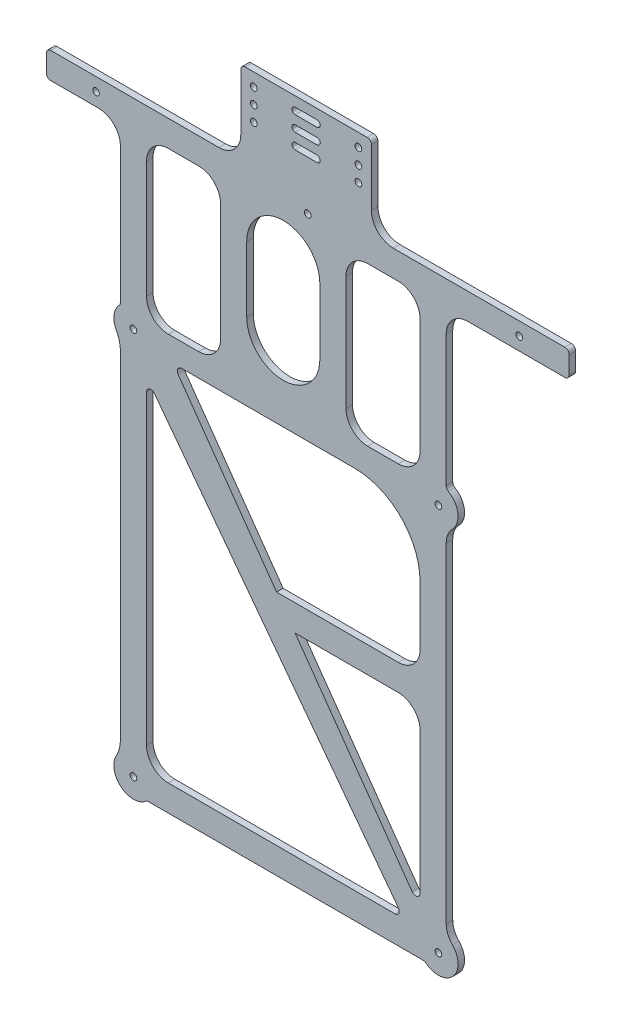
SolidWorks part; units mm, degrees
material "3.3549 (EN-AW 5182)"
ref_plane "前视基准面" through (0, 0, 0) normal (0, 0, 1) x (1, 0, 0)
ref_plane "上视基准面" through (0, 0, 0) normal (0, 1, 0) x (1, 0, 0)
ref_plane "右视基准面" through (0, 0, 0) normal (1, 0, 0) x (0, 0, -1)
other "Configuration Table"
sketch "草图1" plane through (0, 0, 0) normal (0, 0, 1) x (1, 0, 0)
  line L4 (0, 0) -> (0, 0.1191) construction
  line L5 (0, 94.7671) -> (-0.0472, 94.7671) construction
  line L9 (63.5621, 7.8739) -> (63.5621, 94.7671)
  line L10 (60, -5.4329) -> (60, 5.3453) construction
  line L12 (60, -5.4329) -> (51, -5.4329) construction
  line L17 (63.5621, 94.7671) -> (63.5621, 159.1604)
  line L18 (60, 172.4671) -> (80.26, 172.4671) construction
  line L23 (-80, 172.4671) -> (-80, 188.0766) construction
  line L24 (-86, 160.7656) -> (-86, 6.2686)
  line L28 (253.1696, 5.3453) -> (243.1696, 5.3453) construction
  line L29 (-10.7455, 186.263) -> (-10.7455, 172.4671) construction
  line L31 (304, 272.3171) -> (-304, 272.3171) construction
  line L32 (304, 272.3171) -> (304, -82.7829) construction
  line L33 (304, -82.7829) -> (-304, -82.7829) construction
  line L34 (-304, 272.3171) -> (-304, -82.7829) construction
  line L35 (304, 272.3171) -> (0, 94.7671) construction
  line L36 (304, -82.7829) -> (-304, 272.3171) construction
  line L37 (15.2545, 302.3171) -> (-28.7455, 302.3171)
  line L47 (-74, 150.5112) -> (-74, 10.0444)
  line L48 (-64, 0.0444) -> (40.001, 0.0444)
  line L49 (51.5621, 137.9092) -> (51.5621, 110.7671)
  line L50 (-57.898, 167.9092) -> (21.5621, 167.9092)
  line L51 (-70.4034, 151.7157) -> (41.5976, 3.2489)
  line L52 (47.9291, 12.7797) -> (-5.801, 88.7671)
  line L53 (118, 264.2671) -> (39.2545, 264.2671)
  line L54 (118, 252.2671) -> (73.5621, 252.2671)
  line L55 (-120, 262.2671) -> (-120, 254.2671)
  line L56 (120, 262.2671) -> (120, 254.2671)
  line L57 (17.5621, 242.2671) -> (17.5621, 189.674)
  line L58 (-40, 242.2671) -> (-40, 188.4671)
  line L59 (-50.7455, 264.2671) -> (-118, 264.2671)
  line L60 (-50, 252.2671) -> (-64, 252.2671)
  line L61 (63.5621, 242.2671) -> (63.5621, 181.9573)
  line L63 (41.5621, 252.2671) -> (27.5621, 252.2671)
  line L65 (-86, 180.0169) -> (-86, 242.2671)
  line L66 (-96, 252.2671) -> (-118, 252.2671)
  line L67 (41.5621, 100.7671) -> (-14.2861, 100.7671)
  line L68 (41.5621, 88.7671) -> (-5.801, 88.7671)
  line L69 (51.5621, 78.7671) -> (51.5621, 13.9344)
  line L70 (-14.2861, 100.7671) -> (-59.531, 164.7545)
  line L71 (-7.1081, 90.6157) -> (-304, -82.7829) construction
  line L74 (-50, 178.4671) -> (-64, 178.4671)
  line L75 (-74, 242.2671) -> (-74, 188.4671)
  line L76 (27.5621, 179.674) -> (41.5621, 179.674)
  line L78 (51.5621, 242.2671) -> (51.5621, 189.674)
  line L79 (15.2545, 302.3171) -> (19.2545, 302.3171)
  line L80 (-30.7455, 300.3171) -> (-30.7455, 274.2671)
  line L82 (-50.7455, 264.2671) -> (-40.7455, 264.2671)
  line L83 (29.2545, 274.2671) -> (29.2545, 300.3171)
  line L85 (27.2545, 302.3171) -> (19.2545, 302.3171)
  line L86 (52.9494, -11.9556) -> (-73.0456, -11.9556)
  arc A2 (66.4241, 166.1639) -> (64.5508, 180.2318) centre (60, 172.4671) ccw
  arc A4 (-86.5455, 178.6442) -> (-87.8898, 168.1369) centre (-80, 172.4671) ccw
  arc A5 (-87.8898, -1.1027) -> (-74.31, -12.406) centre (-80, -5.4329) ccw
  arc A8 (54.7482, -12.7417) -> (66.4241, 0.8703) centre (60, -5.4329) ccw
  circle A9 centre (0, 258.2671) radius 10.5322 construction
  arc A12 (27.5621, 179.674) -> (17.5621, 189.674) centre (27.5621, 189.674) cw
  arc A13 (-50, 178.4671) -> (-40, 188.4671) centre (-50, 188.4671) ccw
  arc A14 (53.9586, -12.2289) -> (54.7482, -12.7417) centre (48.9128, -20.8625) cw
  arc A15 (63.5621, 7.8739) -> (66.4241, 0.8703) centre (73.5621, 7.8739) ccw
  arc A16 (63.5621, 159.1604) -> (66.4241, 166.1639) centre (73.5621, 159.1604) cw
  arc A19 (-86, 160.7656) -> (-87.8898, 168.1369) centre (-101.3209, 160.7656) ccw
  arc A20 (-86, 6.2686) -> (-87.8898, -1.1027) centre (-101.3209, 6.2686) cw
  arc A22 (-64, 0.0444) -> (-74, 10.0444) centre (-64, 10.0444) cw
  arc A25 (21.5621, 167.9092) -> (51.5621, 137.9092) centre (21.5621, 137.9092) cw
  arc A26 (40.001, 0.0444) -> (41.5976, 3.2489) centre (40.001, 2.0444) ccw
  arc A27 (51.5621, 13.9344) -> (47.9291, 12.7797) centre (49.5621, 13.9344) cw
  arc A28 (-57.898, 167.9092) -> (-59.531, 164.7545) centre (-57.898, 165.9092) ccw
  arc A29 (-74, 150.5112) -> (-70.4034, 151.7157) centre (-72, 150.5112) cw
  arc A32 (-40, 242.2671) -> (-50, 252.2671) centre (-50, 242.2671) ccw
  arc A33 (17.5621, 242.2671) -> (27.5621, 252.2671) centre (27.5621, 242.2671) cw
  arc A34 (118, 264.2671) -> (120, 262.2671) centre (118, 262.2671) cw
  arc A35 (118, 252.2671) -> (120, 254.2671) centre (118, 254.2671) ccw
  arc A36 (-118, 264.2671) -> (-120, 262.2671) centre (-118, 262.2671) ccw
  arc A37 (-118, 252.2671) -> (-120, 254.2671) centre (-118, 254.2671) cw
  arc A38 (-64, 252.2671) -> (-74, 242.2671) centre (-64, 242.2671) ccw
  arc A39 (51.5621, 242.2671) -> (41.5621, 252.2671) centre (41.5621, 242.2671) ccw
  arc A40 (63.5621, 242.2671) -> (73.5621, 252.2671) centre (73.5621, 242.2671) cw
  arc A41 (-86, 242.2671) -> (-96, 252.2671) centre (-96, 242.2671) ccw
  arc A42 (41.5621, 88.7671) -> (51.5621, 78.7671) centre (41.5621, 78.7671) cw
  arc A43 (41.5621, 100.7671) -> (51.5621, 110.7671) centre (41.5621, 110.7671) ccw
  arc A44 (41.5621, 179.674) -> (51.5621, 189.674) centre (41.5621, 189.674) ccw
  arc A45 (-64, 178.4671) -> (-74, 188.4671) centre (-64, 188.4671) cw
  arc A46 (39.2545, 264.2671) -> (29.2545, 274.2671) centre (39.2545, 274.2671) cw
  arc A47 (-30.7455, 274.2671) -> (-40.7455, 264.2671) centre (-40.7455, 274.2671) cw
  arc A48 (-28.7455, 302.3171) -> (-30.7455, 300.3171) centre (-28.7455, 300.3171) ccw
  arc A49 (29.2545, 300.3171) -> (27.2545, 302.3171) centre (27.2545, 300.3171) ccw
  arc A50 (52.9494, -11.9556) -> (53.9586, -12.2289) centre (52.9494, -13.9556) cw
  arc A51 (-74.31, -12.406) -> (-73.0456, -11.9556) centre (-73.0456, -13.9556) cw
  arc A52 (-86, 180.0169) -> (-86.5455, 178.6442) centre (-88, 180.0169) cw
  arc A53 (64.5508, 180.2318) -> (63.5621, 181.9573) centre (65.5621, 181.9573) cw
  point P23 (-40.7455, 272.3171)
  point P39 (-10.7455, 178.4671)
  point P41 (0, 94.7671)
  point P48 (19.2545, 272.3171)
  point P58 (19.2545, 302.3171)
  point P66 (68.1803, -1.6803)
  point P71 (50.8539, 179.674)
  point P76 (-86, 165.7589)
  point P79 (-86, 1.2753)
  point P99 (-30.7455, 302.3171)
  point P101 (-40.7455, 264.2671)
  point P104 (-40, 252.2671)
  point P126 (53.2545, 252.2671)
  point P131 (-86, 252.2671)
  point P135 (-30.7455, 302.3171)
  point P144 (51.5621, 88.7671)
  dimension "D4" = 18
  dimension "D8" = 9
  dimension "D10" = 18
  dimension "D11" = 163.5
  dimension "D17" = 10
  dimension "D18" = 2
  dimension "D19" = 10
  dimension "D20" = 10
  dimension "D21" = 6
  dimension "D22" = 2
  dimension "D23" = 30
  dimension "D29" = 12
  dimension "D30" = 2
  dimension "D31" = 10
  dimension "D32" = 10
  dimension "D35" = 10
  dimension "D7" = 10
  dimension "D24" = 9
  dimension "D36" = 100.2
  dimension "D25" = 12
  dimension "D37" = 2
  dimension "D5" = 2
  dimension "D2" = 60
  dimension "D3" = 100.2
  dimension "D6" = 77.7
  dimension "D9" = 80
  dimension "D12" = 6
  dimension "D13" = 10
  dimension "D14" = 608
  dimension "D15" = 355.1
  dimension "D16" = 30
  dimension "D26" = 6
  dimension "D27" = 120
  dimension "D28" = 120
  dimension "D33" = 6
  dimension "D34" = 6
  dimension "D38" = 80
  dimension "D39" = 77.7
  dimension "D40" = 12
  dimension "D41" = 34
  dimension "D42" = 34
extrude "凸台-拉伸1" add sketch "草图1" against normal blind 3
sketch "草图2" plane through (0, 0, -3) normal (0, 0, -1) x (-1, 0, 0)
  line L0 (0, 176.3264) -> (0, 156.5446) construction
  line L4 (11.219, 233.2671) -> (11.219, 203.2671) construction
  line L5 (28, 233.2671) -> (28, 203.2671)
  line L6 (-5.5621, 233.2671) -> (-5.5621, 203.2671)
  line L9 (40, 188.4671) -> (40, 242.2671) construction
  line L10 (-17.5621, 242.2671) -> (-17.5621, 189.674) construction
  circle A0 centre (-60, 172.4671) radius 1.525
  circle A1 centre (-60, -5.4329) radius 1.525
  circle A2 centre (80, -5.4329) radius 1.525
  circle A3 centre (80, 172.4671) radius 1.525
  circle A5 centre (0, 258.2671) radius 1.55
  arc A6 (28, 233.2671) -> (-5.5621, 233.2671) centre (11.219, 233.2671) ccw
  arc A7 (-5.5621, 203.2671) -> (28, 203.2671) centre (11.219, 203.2671) ccw
  circle A8 centre (-97.15, 258.2671) radius 1.525
  circle A9 centre (97.15, 258.2671) radius 1.525
  point P24 (11.219, 218.2671)
  dimension "D1" = 3.05
  dimension "D2" = 3.05
  dimension "D3" = 3.05
  dimension "D4" = 3.05
  dimension "D5" = 12
  dimension "D7" = 3.1
  dimension "D9" = 60
  dimension "D12" = 3.05
  dimension "D13" = 3.05
  dimension "D6" = 12
  dimension "D8" = 30
  dimension "D10" = 40
  dimension "D11" = 97.15
  dimension "D14" = 97.15
extrude "切除-拉伸1" cut sketch "草图2" against normal through all
sketch "草图3" plane through (0, 0, -3) normal (0, 0, -1) x (-1, 0, 0)
  line L4 (-27.2545, 302.3171) -> (28.7455, 302.3171) construction
  line L6 (-27.2545, 302.3171) -> (28.7455, 302.3171) construction
  line L8 (-4.2545, 296.3171) -> (5.7455, 296.3171) construction
  line L9 (-4.2545, 297.8171) -> (5.7455, 297.8171)
  line L10 (-4.2545, 294.8171) -> (5.7455, 294.8171)
  line L11 (-4.2545, 289.3171) -> (5.7455, 289.3171) construction
  line L12 (-4.2545, 290.8171) -> (5.7455, 290.8171)
  line L13 (-4.2545, 287.8171) -> (5.7455, 287.8171)
  line L14 (-4.2545, 282.3171) -> (5.7455, 282.3171) construction
  line L15 (-4.2545, 283.8171) -> (5.7455, 283.8171)
  line L16 (-4.2545, 280.8171) -> (5.7455, 280.8171)
  line L18 (30.7455, 300.3171) -> (30.7455, 274.2671) construction
  circle A0 centre (-23.2545, 296.3171) radius 1.55
  circle A1 centre (24.7455, 296.3171) radius 1.55
  circle A2 centre (-23.2545, 289.3171) radius 1.55
  circle A3 centre (24.7455, 289.3171) radius 1.55
  circle A4 centre (-23.2545, 282.3171) radius 1.55
  circle A5 centre (24.7455, 282.3171) radius 1.55
  arc A6 (-4.2545, 297.8171) -> (-4.2545, 294.8171) centre (-4.2545, 296.3171) ccw
  arc A7 (5.7455, 294.8171) -> (5.7455, 297.8171) centre (5.7455, 296.3171) ccw
  arc A8 (-4.2545, 290.8171) -> (-4.2545, 287.8171) centre (-4.2545, 289.3171) ccw
  arc A9 (5.7455, 287.8171) -> (5.7455, 290.8171) centre (5.7455, 289.3171) ccw
  arc A10 (-4.2545, 283.8171) -> (-4.2545, 280.8171) centre (-4.2545, 282.3171) ccw
  arc A11 (5.7455, 280.8171) -> (5.7455, 283.8171) centre (5.7455, 282.3171) ccw
  point P22 (0.7455, 296.3171)
  point P30 (0.7455, 289.3171)
  point P37 (0.7455, 282.3171)
  dimension "D1" = 3.1
  dimension "D2" = 3.1
  dimension "D10" = 10
  dimension "D3" = 6
  dimension "D5" = 6
  dimension "D6" = 6
  dimension "D8" = 48
  dimension "D9" = 3
  dimension "D7" = 3
  dimension "D11" = 3
extrude "切除-拉伸2" cut sketch "草图3" against normal through all
